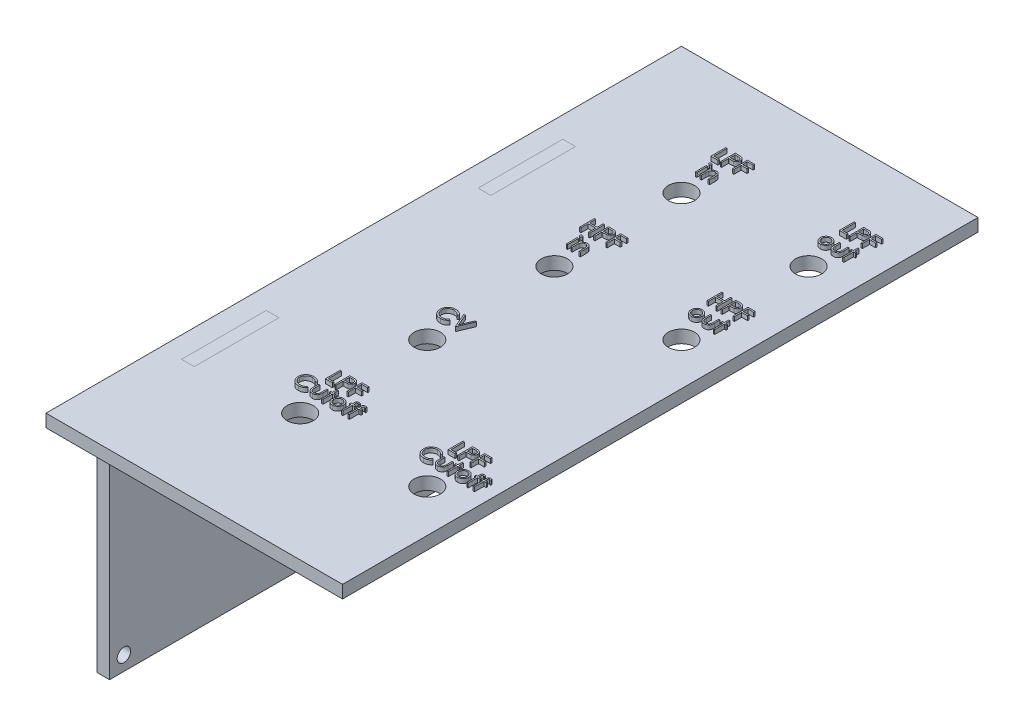
SolidWorks part; units mm, degrees
ref_plane "Front Plane" through (0, 0, 0) normal (0, 0, 1) x (1, 0, 0)
ref_plane "Top Plane" through (0, 0, 0) normal (0, 1, 0) x (1, 0, 0)
ref_plane "Right Plane" through (0, 0, 0) normal (1, 0, 0) x (0, 0, -1)
sketch "Sketch1" plane through (0, 0, 0) normal (0, 1, 0) x (1, 0, 0)
  line L0 (30, 0) -> (30, -50000) construction
  line L1 (0, 0) -> (70, 0)
  line L2 (0, 0) -> (0, -150)
  line L3 (0, -150) -> (70, -150)
  line L4 (70, 0) -> (70, -150)
  line L5 (60, 0) -> (60, -50000) construction
  line L6 (0, -30) -> (50000, -30) construction
  line L7 (0, -60) -> (50000, -60) construction
  line L8 (0, -120) -> (50000, -120) construction
  line L9 (0, -90) -> (50000, -90) construction
  line L11 (5, -33) -> (8, -33)
  line L12 (5, -33) -> (5, -53)
  line L13 (5, -53) -> (8, -53)
  line L14 (8, -33) -> (8, -53)
  line L15 (5, -103) -> (8, -103)
  line L16 (5, -103) -> (5, -123)
  line L17 (5, -123) -> (8, -123)
  line L18 (8, -103) -> (8, -123)
  circle A0 centre (30, -30) radius 3.1
  circle A1 centre (60, -30) radius 3.1
  circle A2 centre (60, -60) radius 3.1
  circle A3 centre (30, -60) radius 3.1
  circle A4 centre (30, -90) radius 3.1
  circle A6 centre (30, -120) radius 3.1
  circle A7 centre (60, -120) radius 3.1
  dimension "D9" = 6.2
  dimension "D1" = 150
  dimension "D2" = 70
  dimension "D3" = 30
  dimension "D4" = 30
  dimension "D5" = 30
  dimension "D6" = 30
  dimension "D7" = 30
  dimension "D8" = 30
  dimension "D10" = 20
  dimension "D11" = 20
  dimension "D12" = 50
  dimension "D13" = 33
  dimension "D14" = 5
  dimension "D15" = 3
  dimension "D16" = 5
extrude "Boss-Extrude1" add sketch "Sketch1" along normal blind 3
ref_plane "Plane1" through (5, 0, 0) normal (1, 0, 0) x (0, 0, -1)
sketch "Sketch2" plane through (5, 0, 0) normal (1, 0, 0) x (0, 0, -1)
  line L0 (-14.476, 0) -> (-14.476, -51)
  line L1 (-150, 0) -> (0, 0) construction
  line L2 (-14.476, -51) -> (-143, -51)
  line L4 (-143, -51) -> (-143, 0)
  line L7 (-150, 3) -> (-150, 0) construction
  line L9 (-14.476, 0) -> (-33, 0)
  line L10 (-33, 0) -> (-33, 3)
  line L11 (-33, 3) -> (-53, 3)
  line L12 (-53, 3) -> (-53, 0)
  line L13 (-143, 0) -> (-123, 0)
  line L14 (-123, 0) -> (-123, 3)
  line L15 (-123, 3) -> (-103, 3)
  line L16 (-103, 3) -> (-103, 0)
  line L17 (-103, 0) -> (-53, 0)
  circle A0 centre (-17.87, -3.594) radius 1.6
  circle A1 centre (-17.87, -47.606) radius 1.6
  circle A2 centre (-139.606, -47.606) radius 1.6
  circle A3 centre (-139.606, -3.594) radius 1.6
  dimension "D10" = 3.2
  dimension "D1" = 51
  dimension "D2" = 128.524
  dimension "D3" = 7
  dimension "D4" = 3
  dimension "D5" = 50
  dimension "D6" = 20
  dimension "D7" = 3
  dimension "D8" = 20
  dimension "D9" = 20
  dimension "D11" = 3.394
  dimension "D12" = 3.394
  dimension "D13" = 3.394
  dimension "D14" = 47.406
  dimension "D15" = 3.394
  dimension "D16" = 121.736
  dimension "D17" = 44.012
  dimension "D18" = 121.736
extrude "Boss-Extrude2" add sketch "Sketch2" along normal blind 3 separate body
sketch "Sketch3" plane through (0, 3, 0) normal (0, 1, 0) x (1, 0, 0)
  line L1 (0, 0) -> (0, -150) construction
  line L2 (70, 0) -> (0, 0) construction
  line L4 (0, -150) -> (70, -150) construction
  text T0 "LPF                 LPF\r\n"
  text T1 "in                  out"
  text T2 "HPF                HPF"
  text T3 "in                  out"
  text T4 "CV"
  text T5 "LPF                LPF"
  text T6 "Cutoff           Cutoff"
  dimension "D1" = 26.5
  dimension "D2" = 20
  dimension "D3" = 28
  dimension "D4" = 25
  dimension "D5" = 25.5
  dimension "D6" = 50
  dimension "D7" = 27.5
  dimension "D8" = 55
  dimension "D9" = 26
  dimension "D10" = 65
  dimension "D11" = 26.5
  dimension "D12" = 39
  dimension "D13" = 23
  dimension "D14" = 34.5
extrude "Boss-Extrude3" add sketch "Sketch3" along normal blind 1
